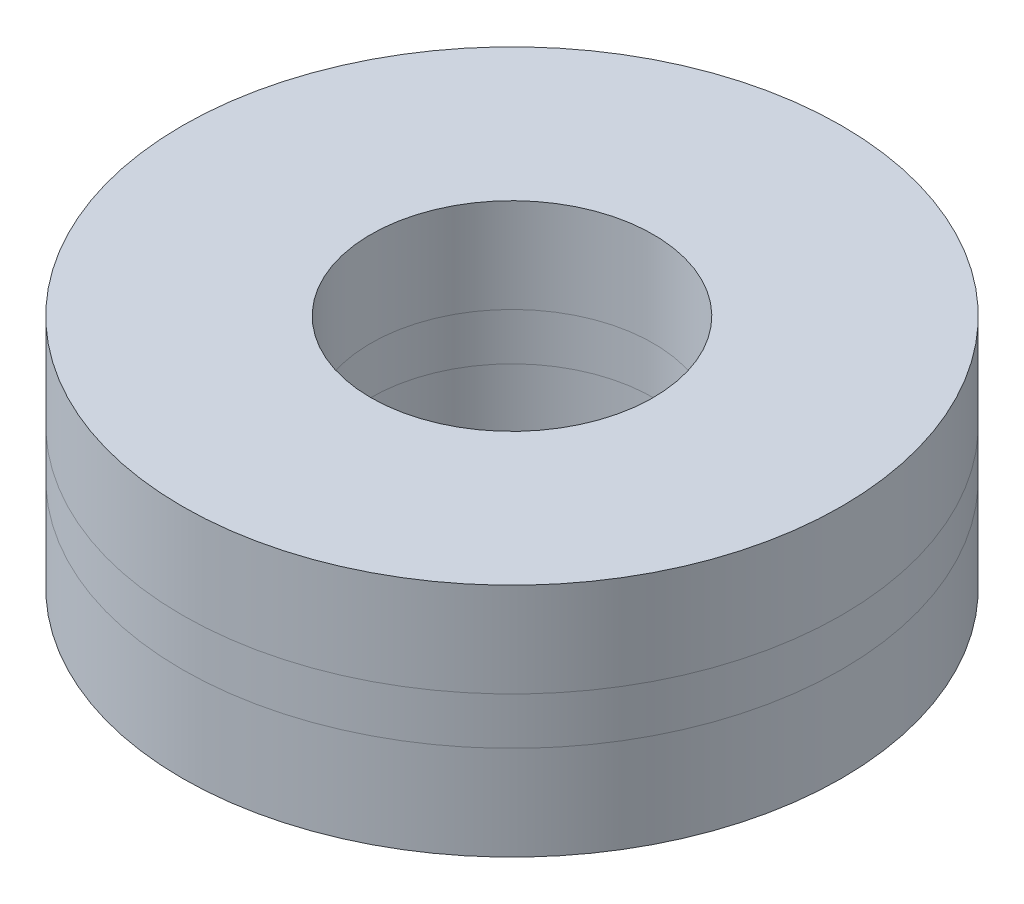
SolidWorks part; units mm, degrees
ref_plane "前视基准面" through (0, 0, 0) normal (0, 0, 1) x (1, 0, 0)
ref_plane "上视基准面" through (0, 0, 0) normal (0, 1, 0) x (1, 0, 0)
ref_plane "右视基准面" through (0, 0, 0) normal (1, 0, 0) x (0, 0, -1)
sketch "草图1" plane through (0, 0, 0) normal (0, 1, 0) x (1, 0, 0)
  circle A0 centre (0, 0) radius 3
  circle A1 centre (0, 0) radius 7
  dimension "D1" = 6
  dimension "D2" = 14
extrude "凸台-拉伸1" add sketch "草图1" along normal blind 2
sketch "草图2" plane through (0, 2, 0) normal (0, 1, 0) x (1, 0, 0)
  circle A0 centre (0, 0) radius 3 construction
  circle A1 centre (0, 0) radius 7
  circle A2 centre (0, 0) radius 7
  circle A3 centre (0, 0) radius 3
  dimension "D1" = 0
extrude "凸台-拉伸2" add sketch "草图2" along normal blind 1 separate body
sketch "草图3" plane through (0, 3, 0) normal (0, 1, 0) x (1, 0, 0)
  circle A0 centre (0, 0) radius 3 construction
  circle A1 centre (0, 0) radius 7
  circle A2 centre (0, 0) radius 7
  circle A3 centre (0, 0) radius 3
  dimension "D1" = 0
extrude "凸台-拉伸3" add sketch "草图3" along normal blind 2 separate body
